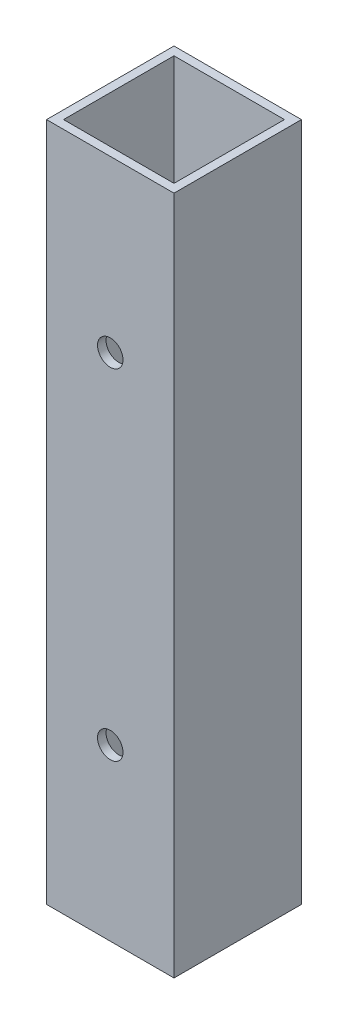
SolidWorks part; units mm, degrees
material "6061-O (SS)"
ref_plane "前视基准面" through (0, 0, 0) normal (0, 0, 1) x (1, 0, 0)
ref_plane "上视基准面" through (0, 0, 0) normal (0, 1, 0) x (1, 0, 0)
ref_plane "右视基准面" through (0, 0, 0) normal (1, 0, 0) x (0, 0, -1)
sketch "草图1" plane through (0, 0, 0) normal (0, 1, 0) x (1, 0, 0)
  line L0 (-6.5, 6.5) -> (6.5, 6.5)
  line L1 (-7.5, -7.5) -> (7.5, -7.5)
  line L2 (-7.5, -7.5) -> (-7.5, 7.5)
  line L3 (-7.5, 7.5) -> (7.5, 7.5)
  line L4 (7.5, -7.5) -> (7.5, 7.5)
  line L5 (-7.5, -7.5) -> (7.5, 7.5) construction
  line L6 (-7.5, 7.5) -> (7.5, -7.5) construction
  line L7 (6.5, -6.5) -> (6.5, 6.5)
  line L8 (-6.5, -6.5) -> (6.5, -6.5)
  line L9 (-6.5, -6.5) -> (-6.5, 6.5)
  point P0 (0, 0)
  dimension "D1" = 15
  dimension "D2" = 1
extrude "凸台-拉伸1" add sketch "草图1" along normal blind 80
sketch "草图2" plane through (0, 0, 7.5) normal (0, 0, 1) x (1, 0, 0)
  line L0 (0, 0) -> (0, 80) construction
  line L1 (-7.5, 80) -> (7.5, 80) construction
  line L2 (-7.5, 40) -> (7.5, 40) construction
  line L3 (-7.5, 80) -> (-7.5, 0) construction
  line L4 (7.5, 80) -> (7.5, 0) construction
  circle A0 centre (0, 60) radius 1.5
  circle A1 centre (0, 20) radius 1.5
  dimension "D1" = 40
  dimension "D2" = 3
extrude "切除-拉伸1" cut sketch "草图2" against normal through all
